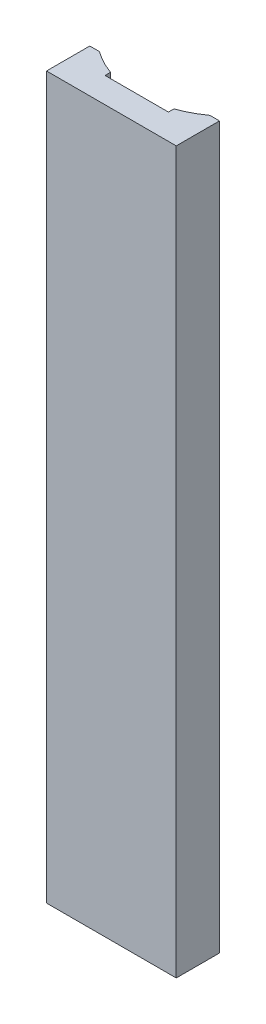
SolidWorks part; units mm, degrees
ref_plane "Ebene vorne" through (0, 0, 0) normal (0, 0, 1) x (1, 0, 0)
ref_plane "Ebene oben" through (0, 0, 0) normal (0, 1, 0) x (1, 0, 0)
ref_plane "Ebene rechts" through (0, 0, 0) normal (1, 0, 0) x (0, 0, -1)
sketch "Skizze1" plane through (0, 0, 0) normal (0, 1, 0) x (1, 0, 0)
  line L0 (-32.248, 0) -> (72.9564, 0) construction
  line L1 (-22.5, 7.5) -> (22.5, 7.5)
  line L2 (-22.5, 7.5) -> (-22.5, -7.5)
  line L3 (-22.5, -7.5) -> (22.5, -7.5)
  line L4 (22.5, 7.5) -> (22.5, -7.5)
  line L5 (0, 40.3012) -> (0, -36.3862) construction
  circle A0 centre (0, 34) radius 32.7
  point P11 (0, 23.9636)
  point P12 (0, 35.9263)
  point P13 (0, 33.9438)
  point P14 (0, 40.3012)
  dimension "D3" = 65.4
  dimension "D1" = 45
  dimension "D2" = 15
  dimension "D4" = 34
extrude "Rundung" add sketch "Skizze1" along normal blind 250 contours A0 L1 L2 L3 L4
sketch "Skizze2" plane through (0, 250, 0) normal (0, 1, 0) x (1, 0, 0)
  line L0 (0, 0) -> (0, 7.7395) construction
  line L1 (-11, 4.5707) -> (11, 4.5707)
  line L2 (-11, 4.5707) -> (-11, 1.3)
  line L3 (-11, 1.3) -> (11, 1.3)
  line L4 (11, 4.5707) -> (11, 1.3)
  line L5 (0, 7.7395) -> (0, -13.5524) construction
  arc A0 (-19.1583, 7.5) -> (19.1583, 7.5) centre (0, 34) ccw construction
  point P7 (0, 1.3)
  dimension "D1" = 22
extrude "AussparungLauf" cut sketch "Skizze2" against normal through all
